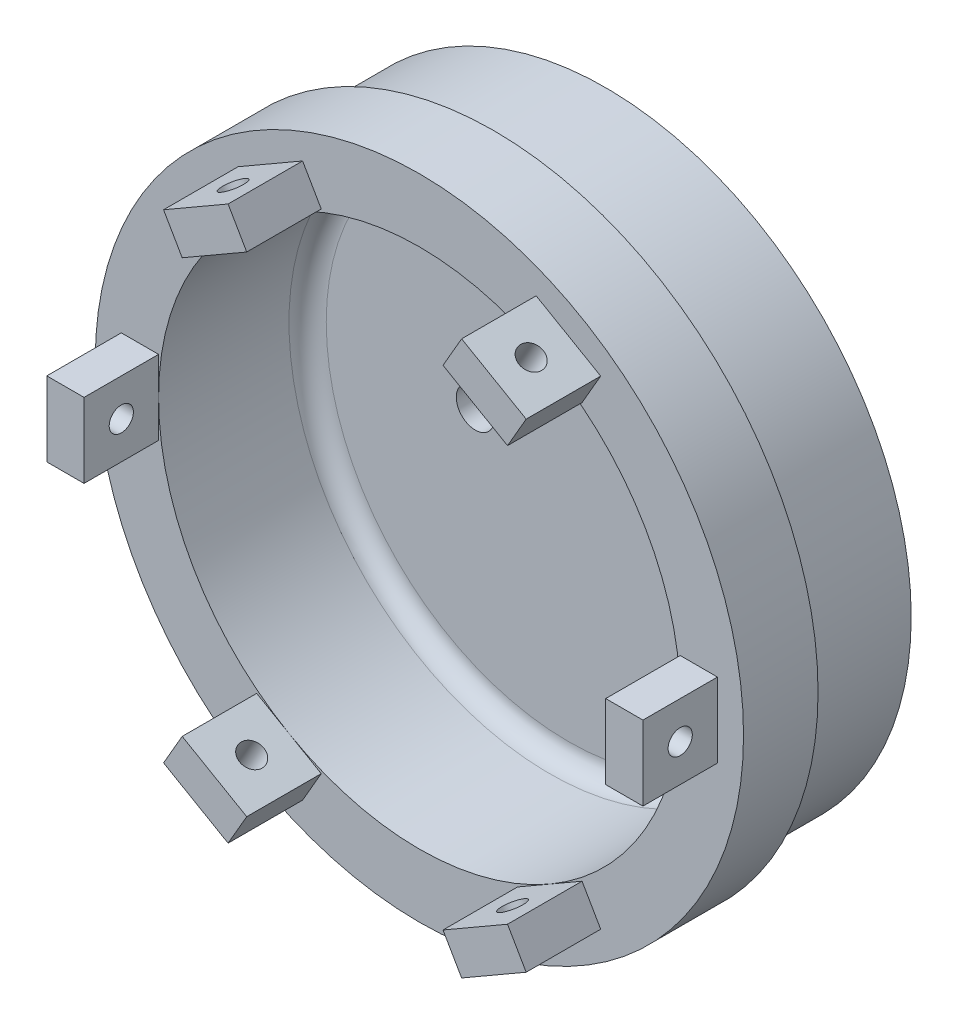
SolidWorks part; units mm, degrees
ref_plane "Front Plane" through (0, 0, 0) normal (0, 0, 1) x (1, 0, 0)
ref_plane "Top Plane" through (0, 0, 0) normal (0, 1, 0) x (1, 0, 0)
ref_plane "Right Plane" through (0, 0, 0) normal (1, 0, 0) x (0, 0, -1)
sketch "Sketch1" plane through (0, 0, 0) normal (0, 1, 0) x (1, 0, 0)
  line L0 (0, 0) -> (0, 163.3252) construction
  line L1 (0, 0) -> (82, 0)
  line L2 (82, 0) -> (82, -30)
  line L3 (82, -30) -> (87, -30)
  line L4 (87, -30) -> (87, -50)
  line L5 (87, -50) -> (70, -50)
  line L6 (70, -50) -> (70, -15)
  line L7 (65, -10) -> (0, -10)
  line L8 (0, -10) -> (0, 0)
  arc A0 (70, -15) -> (65, -10) centre (65, -15) ccw
  point P12 (70, -10)
  dimension "D1" = 40
  dimension "D7" = 5
  dimension "D2" = 20
  dimension "D3" = 30
  dimension "D4" = 82
  dimension "D5" = 87
  dimension "D6" = 70
revolve "Revolve1" add sketch "Sketch1" angle 360 about L0
sketch "Sketch3" plane through (0, 0, 0) normal (0, 0, -1) x (-1, 0, 0)
  circle A0 centre (-25, 0) radius 5.1
  circle A1 centre (25, 0) radius 5.1
  circle A2 centre (0, 0) radius 65 construction
  arc A4 (10.5925, 60.0733) -> (11.9817, 67.9517) centre (11.2871, 64.0125) ccw
  arc A5 (-11.9817, 67.9517) -> (-10.5925, 60.0733) centre (-11.2871, 64.0125) ccw
  arc A6 (10.5925, 60.0733) -> (-10.5925, 60.0733) centre (0, 0) ccw
  arc A7 (11.9817, 67.9517) -> (-11.9817, 67.9517) centre (0, 0) ccw
  dimension "D1" = 50
  dimension "D2" = 25
extrude "Cut-Extrude1" cut sketch "Sketch3" against normal up to next
sketch "Sketch5" plane through (0, 0, 50) normal (0, 0, 1) x (1, 0, 0)
  line L9 (80, 10) -> (80, 0)
  line L10 (70, 10) -> (80, 10)
  line L11 (80, 0) -> (80, -10)
  line L12 (80, -10) -> (70, -10)
  line L13 (70, -10) -> (70, 10)
extrude "Boss-Extrude3" add sketch "Sketch5" along normal blind 20
sketch "Sketch6" plane through (80, 0, 0) normal (-1, 0, 0) x (0, 1, 0)
  line L0 (-10, -70) -> (-10, -50) construction
  line L3 (10, -70) -> (-10, -70) construction
  circle A1 centre (0, -60) radius 3.25
  dimension "D1" = 10
  dimension "D3" = 6.5
  dimension "D2" = 10
extrude "Cut-Extrude2" cut sketch "Sketch6" along normal up to next
fillet "Fillet1" [suppressed] radius 2
pattern_circular "CirPattern1" count 6 over 360 about axis through (0, 0, 0) along (0, 0, 1) of "Boss-Extrude3", "Cut-Extrude2", "Fillet1"
